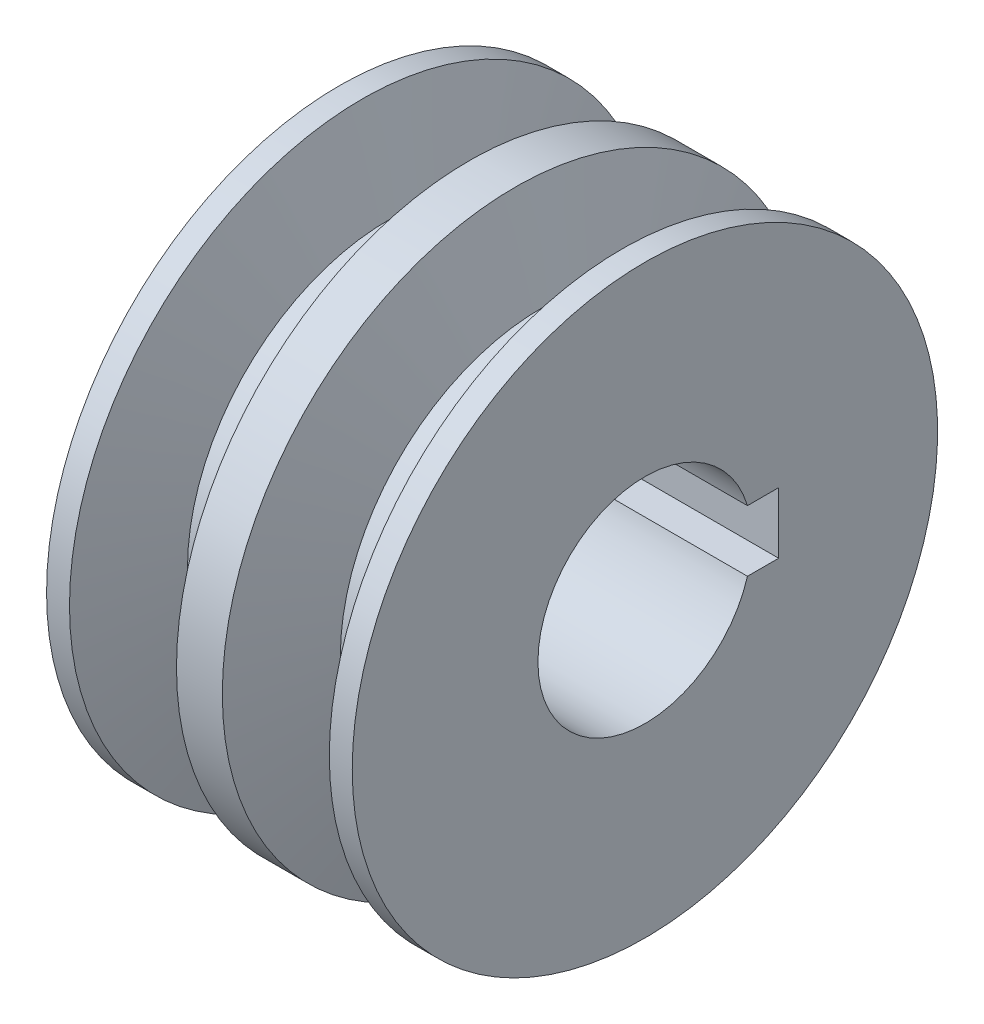
SolidWorks part; units mm, degrees
ref_plane "Ön Düzlem" through (0, 0, 0) normal (0, 0, 1) x (1, 0, 0)
ref_plane "Üst Düzlem" through (0, 0, 0) normal (0, 1, 0) x (1, 0, 0)
ref_plane "Sağ Düzlem" through (0, 0, 0) normal (1, 0, 0) x (0, 0, -1)
ref_plane "Düzlem1" through (0, 0, 414.673) normal (0, 0, -1) x (-1, 0, 0)
sketch "Çizim1" plane through (0, 0, 414.673) normal (0, 0, -1) x (-1, 0, 0)
  line L0 (-985.2541, 38.3) -> (-985.2541, 0)
  line L1 (-985.2541, 0) -> (-945.2541, 0)
  line L2 (-945.2541, 0) -> (-945.2541, 38.3)
  line L3 (-945.2541, 38.3) -> (-948.2541, 38.3)
  line L4 (-948.2541, 38.3) -> (-951.6951, 26.3)
  line L5 (-951.6951, 26.3) -> (-958.8132, 26.3)
  line L6 (-958.8132, 26.3) -> (-962.2541, 38.3)
  line L7 (-962.2541, 38.3) -> (-968.2541, 38.3)
  line L8 (-968.2541, 38.3) -> (-971.6951, 26.3)
  line L9 (-971.6951, 26.3) -> (-978.8132, 26.3)
  line L10 (-978.8132, 26.3) -> (-982.2541, 38.3)
  line L11 (-982.2541, 38.3) -> (-985.2541, 38.3)
  line L12 (-985.2541, 0) -> (-945.2541, 0) construction
revolve "Döndür1" add sketch "Çizim1" angle 360 about L12
sketch "Çizim2" plane through (945.2541, 0, 0) normal (-1, 0, 0) x (0, 0, 1)
  line L0 (405.6592, 3) -> (402.173, 3)
  line L1 (402.173, 3) -> (402.173, -3)
  line L2 (402.173, -3) -> (405.6592, -3)
  arc A0 (405.6592, -3) -> (405.6592, 3) centre (414.673, 0) ccw
extrude "Kes-Ekstrüzyon1" cut sketch "Çizim2" against normal through all
sketch "Çizim3" plane through (985.2541, 0, 0) normal (1, 0, 0) x (0, 0, -1)
  circle A0 centre (-414.673, 0) radius 14
extrude "Kes-Ekstrüzyon2" cut sketch "Çizim3" against normal blind 40
sketch "Çizim4" plane through (985.2541, 0, 0) normal (1, 0, 0) x (0, 0, -1)
  line L0 (-414.673, 0) -> (-400.673, 0)
  line L1 (-400.673, 0) -> (-400.673, -4)
  line L2 (-400.673, -4) -> (-400.673, 4)
  line L3 (-400.673, 4) -> (-397.173, 4)
  line L4 (-397.173, 4) -> (-402.0683, 4)
  line L5 (-397.173, 4) -> (-397.173, -4)
  line L6 (-397.173, -4) -> (-401.9295, -4)
  circle A0 centre (-414.673, 0) radius 14
  circle M5 centre (-414.673, 0) radius 14
extrude "Kes-Ekstrüzyon3" cut sketch "Çizim4" against normal blind 40 contours L6 L5 L3 L2 L1 | L2 L4 M5 | L6 L1 M5
